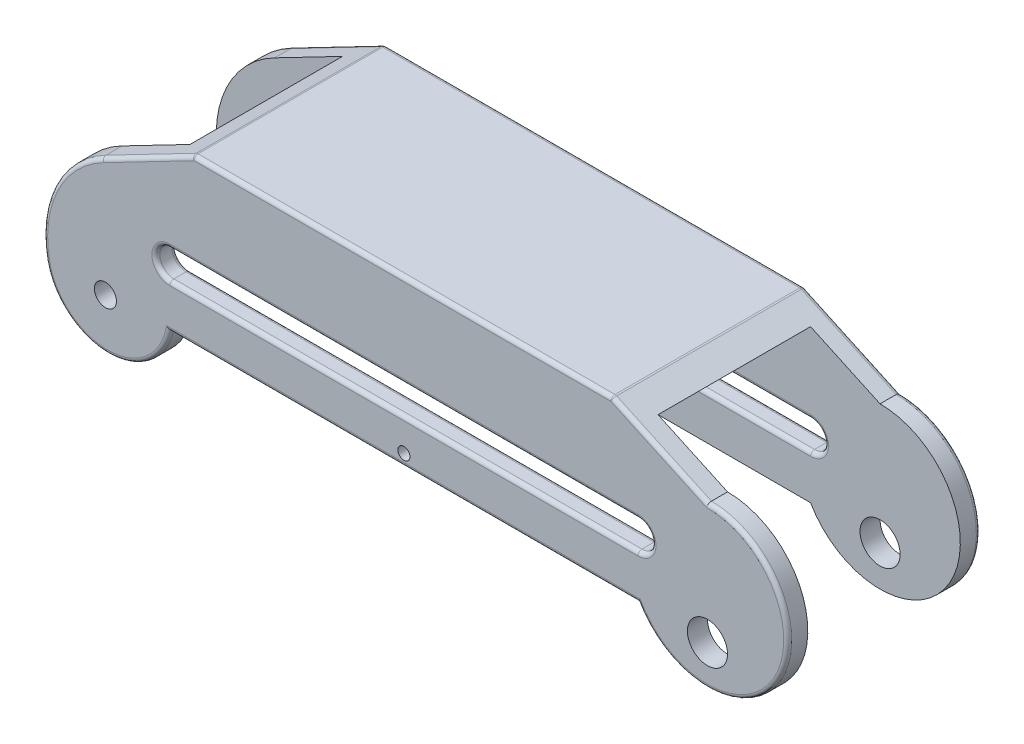
SolidWorks part; units mm, degrees
ref_plane "Front Plane" through (0, 0, 0) normal (0, 0, 1) x (1, 0, 0)
ref_plane "Top Plane" through (0, 0, 0) normal (0, 1, 0) x (1, 0, 0)
ref_plane "Right Plane" through (0, 0, 0) normal (1, 0, 0) x (0, 0, -1)
sketch "Sketch1" plane through (0, 0, 0) normal (0, 0, 1) x (1, 0, 0)
  line L0 (-58.3087, -15) -> (-89.2173, -15) construction
  line L1 (-58.3087, -15) -> (58.3087, -15)
  line L5 (-74.3708, 5.1315) -> (-74.3708, -26.8454) construction
  line L6 (58.3087, -15) -> (75.6292, -15) construction
  line L7 (-58.3087, -4.0039) -> (58.3087, -4.0039)
  line L8 (58.3087, -0.5039) -> (58.3087, -15) construction
  line L9 (-58.3087, 2.9961) -> (58.3087, 2.9961)
  line L10 (-58.3087, 22.9961) -> (58.3087, 22.9961)
  line L11 (75.6292, -5) -> (75.6292, 15) construction
  line L12 (-58.3087, -15) -> (-58.3087, -4.0039) construction
  line L13 (75.6292, 15) -> (58.3087, 22.9961)
  line L14 (75.6292, -15) -> (75.6292, -10) construction
  line L15 (75.6292, -15) -> (75.6292, -5) construction
  line L16 (-58.3087, 22.9961) -> (-75.2437, 14.2129)
  arc A1 (75.6292, 15) -> (58.3087, -15) centre (75.6292, -5) cw
  circle A2 centre (-74.3708, -15) radius 5.5
  circle A3 centre (-74.3708, -7) radius 1.5
  circle A5 centre (75.6292, -15) radius 5
  circle A6 centre (0, -12) radius 1.5
  arc A10 (-58.3087, 2.9961) -> (-58.3087, -4.0039) centre (-58.3087, -0.5039) ccw
  arc A11 (58.3087, 2.9961) -> (58.3087, -4.0039) centre (58.3087, -0.5039) cw
  circle A13 centre (-66.3708, -15) radius 1.5
  circle A14 centre (-74.3708, -23) radius 1.5
  circle A15 centre (-82.3708, -15) radius 1.5
  arc A16 (-58.3087, -15) -> (-89.2173, -15) centre (-73.763, -11.8269) cw
  arc A17 (-89.2173, -15) -> (-75.2437, 14.2129) centre (-62.9636, -9.6096) cw
  point P49 (-74.3708, -15)
  dimension "D1" = 20
  dimension "D3" = 8
  dimension "D5" = 10
  dimension "D6" = 11
  dimension "D9" = 3
  dimension "D4" = 7
  dimension "D7" = 4
  dimension "D8" = 150
  dimension "D10" = 3
  dimension "D11" = 20
extrude "Boss-Extrude1" add sketch "Sketch1" along normal blind 5
ref_plane "Plane1" through (0, 0, 43) normal (0, 0, 1) x (1, 0, 0)
sketch "Sketch2" plane through (0, 0, 43) normal (0, 0, 1) x (1, 0, 0)
  line L2 (-58.3087, -4.0039) -> (58.3087, -4.0039)
  line L3 (58.3087, 2.9961) -> (-58.3087, 2.9961)
  line L4 (-58.3087, -4.0039) -> (58.3087, -4.0039)
  line L5 (58.3087, 2.9961) -> (-58.3087, 2.9961)
  line L8 (75.6292, 15) -> (58.3087, 22.9961)
  line L10 (-58.3087, -15) -> (58.3087, -15)
  line L11 (58.3087, 22.9961) -> (-58.3087, 22.9961)
  line L12 (58.3087, 22.9961) -> (-58.3087, 22.9961)
  line L13 (-58.3087, 22.9961) -> (-75.2437, 14.2129)
  line L14 (-58.3087, 22.9961) -> (-75.2437, 14.2129)
  line L16 (-58.3087, -15) -> (58.3087, -15)
  line L17 (75.6292, 15) -> (58.3087, 22.9961)
  circle A0 centre (-74.3708, -15) radius 2.75
  circle A1 centre (75.6292, -15) radius 5
  arc A2 (-58.3087, 2.9961) -> (-58.3087, -4.0039) centre (-58.3087, -0.5039) ccw
  arc A3 (58.3087, -4.0039) -> (58.3087, 2.9961) centre (58.3087, -0.5039) ccw
  arc A4 (-58.3087, 2.9961) -> (-58.3087, -4.0039) centre (-58.3087, -0.5039) ccw
  arc A5 (58.3087, -4.0039) -> (58.3087, 2.9961) centre (58.3087, -0.5039) ccw
  circle A6 centre (75.6292, -15) radius 5
  circle A11 centre (0, -12) radius 1.5
  circle A12 centre (0, -12) radius 1.5
  arc A17 (-89.2173, -15) -> (-58.3087, -15) centre (-73.763, -11.8269) ccw
  arc A18 (58.3087, -15) -> (75.6292, 15) centre (75.6292, -5) ccw
  arc A19 (-89.2173, -15) -> (-58.3087, -15) centre (-73.763, -11.8269) ccw
  arc A23 (-75.2437, 14.2129) -> (-89.2173, -15) centre (-62.9636, -9.6096) ccw
  arc A24 (-75.2437, 14.2129) -> (-89.2173, -15) centre (-62.9636, -9.6096) ccw
  arc A26 (58.3087, -15) -> (75.6292, 15) centre (75.6292, -5) ccw
  dimension "D3" = 5.5
  dimension "D1" = 0
  dimension "D2" = 0
  dimension "D5" = 0
  dimension "D7" = 0
extrude "Boss-Extrude2" add sketch "Sketch2" along normal blind 5
sketch "Sketch5" plane through (0, 0, 48) normal (0, 0, 1) x (1, 0, 0)
  line L0 (-58.3087, 22.9961) -> (-52.5243, 25.9961)
  line L1 (-52.5243, 25.9961) -> (51.8103, 25.9961)
  line L2 (51.8103, 25.9961) -> (58.3087, 22.9961)
  line L3 (75.6292, 15) -> (58.3087, 22.9961) construction
  line L4 (58.3087, 22.9961) -> (-58.3087, 22.9961) construction
  line L5 (-58.3087, 22.9961) -> (-75.2437, 14.2129) construction
  line L6 (-58.3087, 22.9961) -> (58.3087, 22.9961)
  dimension "D1" = 3
extrude "Boss-Extrude4" add sketch "Sketch5" against normal up to vertex
fillet "Fillet1" radius 1 32 edges at (0, -15, 0) (92.9497, -15, 0) (63.7198, 20.4981, 0) (-63.884, 20.1045, 0) (-87.1413, 1.9555, 0) (-73.763, -27.6036, 0) (61.8087, -0.5039, 0) (0, -4.0039, 0) (-61.8087, -0.5039, 0) (0, 2.9961, 0) (-52.5243, 25.9961, 24) (-0.357, 25.9961, 48) (-0.357, 25.9961, 0) (51.8103, 25.9961, 24) (-61.8087, -0.5039, 48) (0, -4.0039, 48) (61.8087, -0.5039, 48) (0, 2.9961, 48) (63.7198, 20.4981, 48) (92.9497, -15, 48) (0, -15, 48) (-73.763, -27.6036, 48) (-87.1413, 1.9555, 48) (-63.884, 20.1045, 48) (-61.8087, -0.5039, 5) (0, 2.9961, 5) (61.8087, -0.5039, 5) (-61.8087, -0.5039, 43) (0, 2.9961, 43) (61.8087, -0.5039, 43) (0, -4.0039, 5) (0, -4.0039, 43)
ref_plane "Plane2" through (-58.3087, 0, 0) normal (1, 0, 0) x (0, 0, -1)
ref_plane "Plane3" through (58.3087, 0, 0) normal (1, 0, 0) x (0, 0, -1)
sketch "Sketch7" plane through (58.3087, 0, 0) normal (1, 0, 0) x (0, 0, -1)
  line L1 (-5, 22.9961) -> (-43, 22.9961) construction
  line L9 (-5, 14.9961) -> (-15, 14.9961)
  line L10 (-5, 15) -> (-5, -25) construction
  line L11 (-15, 14.9961) -> (-15, 22.9961)
  line L12 (-15, 22.9961) -> (-18, 22.9961)
  line L13 (-18, 22.9961) -> (-18, 11.9961)
  line L14 (-18, 11.9961) -> (-5, 11.9961)
  line L15 (-5, 15) -> (-5, 22.9961) construction
  line L17 (-5, 14.9961) -> (-5, 11.9961)
  dimension "D5" = 3
  dimension "D6" = 3
  dimension "D7" = 8
  dimension "D8" = 10
extrude "Boss-Extrude5" add sketch "Sketch7" against normal blind 3 from offset 16 offset against normal yes
fillet "Fillet2" radius 2 2 edges at (40.8087, 14.9961, 15) (40.8087, 11.9961, 18)
pattern_linear "LPattern1" count 3 spacing 40 along (-1, 0, 0) of "Fillet2", "Boss-Extrude5"
